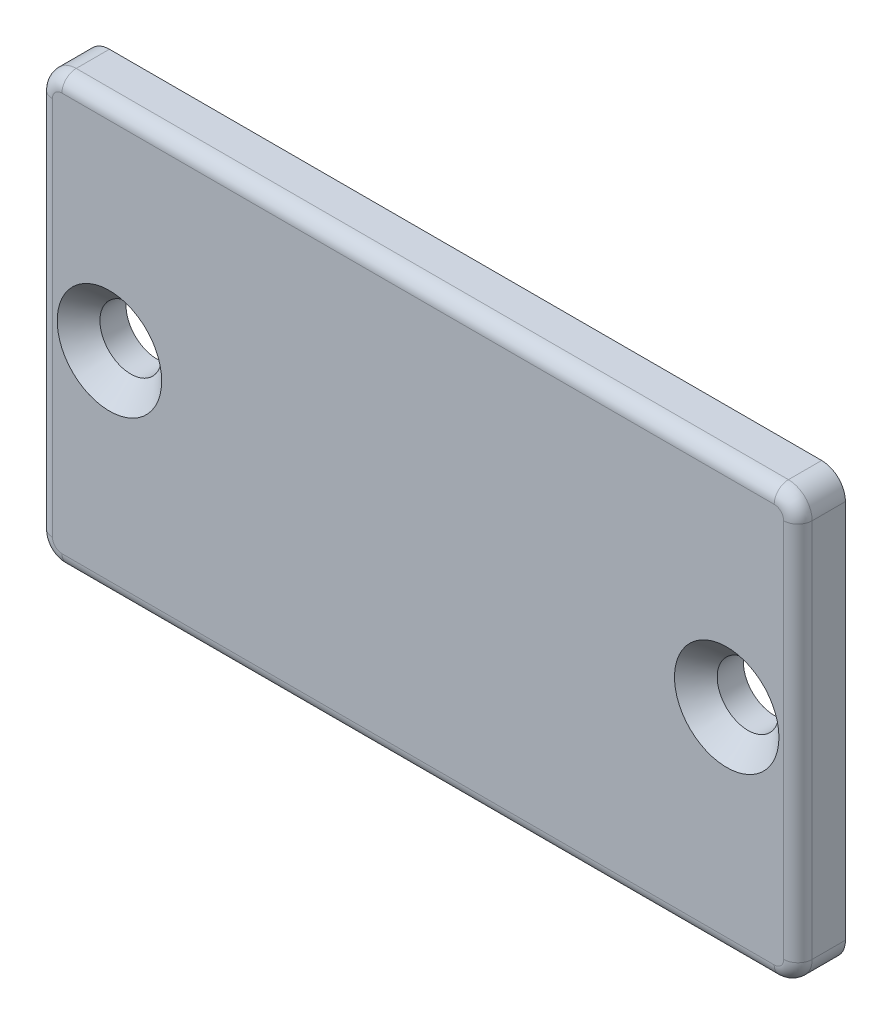
SolidWorks part; units mm, degrees
ref_plane "Plan de face" through (0, 0, 0) normal (0, 0, 1) x (1, 0, 0)
ref_plane "Plan de dessus" through (0, 0, 0) normal (0, 1, 0) x (1, 0, 0)
ref_plane "Plan de droite" through (0, 0, 0) normal (1, 0, 0) x (0, 0, -1)
sketch "Esquisse1" plane through (0, 0, 0) normal (0, 0, 1) x (1, 0, 0)
  line L1 (-16, -9) -> (16, -9)
  line L2 (-16, -9) -> (-16, 9)
  line L3 (-16, 9) -> (16, 9)
  line L4 (16, -9) -> (16, 9)
  line L5 (-16, -9) -> (16, 9) construction
  line L6 (-16, 9) -> (16, -9) construction
  point P0 (0, 0)
  dimension "D1" = 32
  dimension "D2" = 18
extrude "Boss.-Extru.1" add sketch "Esquisse1" along normal blind 2
sketch "Esquisse2" plane through (0, 0, 0) normal (0, 0, -1) x (-1, 0, 0)
  line L0 (-16, 9) -> (16, 9) construction
  line L1 (-9.5, -6) -> (9.5, -6)
  line L2 (-9.5, -6) -> (-9.5, 6)
  line L3 (-9.5, 6) -> (9.5, 6)
  line L4 (9.5, -6) -> (9.5, 6)
  line L5 (-9.5, -6) -> (9.5, 6) construction
  line L6 (-9.5, 6) -> (9.5, -6) construction
  point P0 (0, 0)
  dimension "D1" = 3
  dimension "D2" = 19
extrude "Boss.-Extru.2" add sketch "Esquisse2" along normal blind 1.4
fillet "Congé1" radius 1 4 edges at (16, -9, 1) (-16, -9, 1) (-16, 9, 1) (16, 9, 1)
fillet "Congé2" radius 0.6 8 edges at (-15.7071, -8.7071, 2) (-16, 0, 2) (-15.7071, 8.7071, 2) (0, 9, 2) (15.7071, 8.7071, 2) (16, 0, 2) (15.7071, -8.7071, 2) (0, -9, 2)
fillet "Congé3" radius 1 4 edges at (9.5, -6, -0.7) (-9.5, -6, -0.7) (-9.5, 6, -0.7) (9.5, 6, -0.7)
hole_wizard "Fraisage pour vis à tête fraisée M21" positions "Esquisse4" profile "Esquisse5" countersink size "M2" standard "ISO" end condition through all
sketch "Esquisse4" plane through (0, 0, 2) normal (0, 0, 1) x (1, 0, 0)
  line L0 (-16, 0) -> (16, 0) construction
  line L1 (-16, -8) -> (-16, 8) construction
  line L2 (16, 8) -> (16, -8) construction
  point P0 (-13, 0)
  dimension "D1" = 13
sketch "Esquisse5" plane through (-13, 0, 2) normal (1, 0, 0) x (0, -1, 0)
  line L0 (0, 0) -> (0, 3.4)
  line L1 (0, 3.4) -> (1.3, 3.4)
  line L2 (1.3, 3.4) -> (1.3, 0.9)
  line L3 (1.3, 0.9) -> (2.2, 0)
  line L5 (2.2, 0) -> (0, 0)
  line L6 (-1.3, 0.9) -> (-2.2, 0) construction
  line L11 (0, -6.35) -> (0, 107.95) construction
  dimension "Diamètre du perçage jusqu'au prochain" = 2.6
  dimension "Profondeur du perçage jusqu'au prochain" = 3.4
  dimension "Diamètre du fraisage entrant" = 4.4
  dimension "Angle du fraisage entrant" = 90
mirror "Symétrie1" about plane through (0, 0, 0) normal (1, 0, 0) of "Fraisage pour vis à tête fraisée M21"
